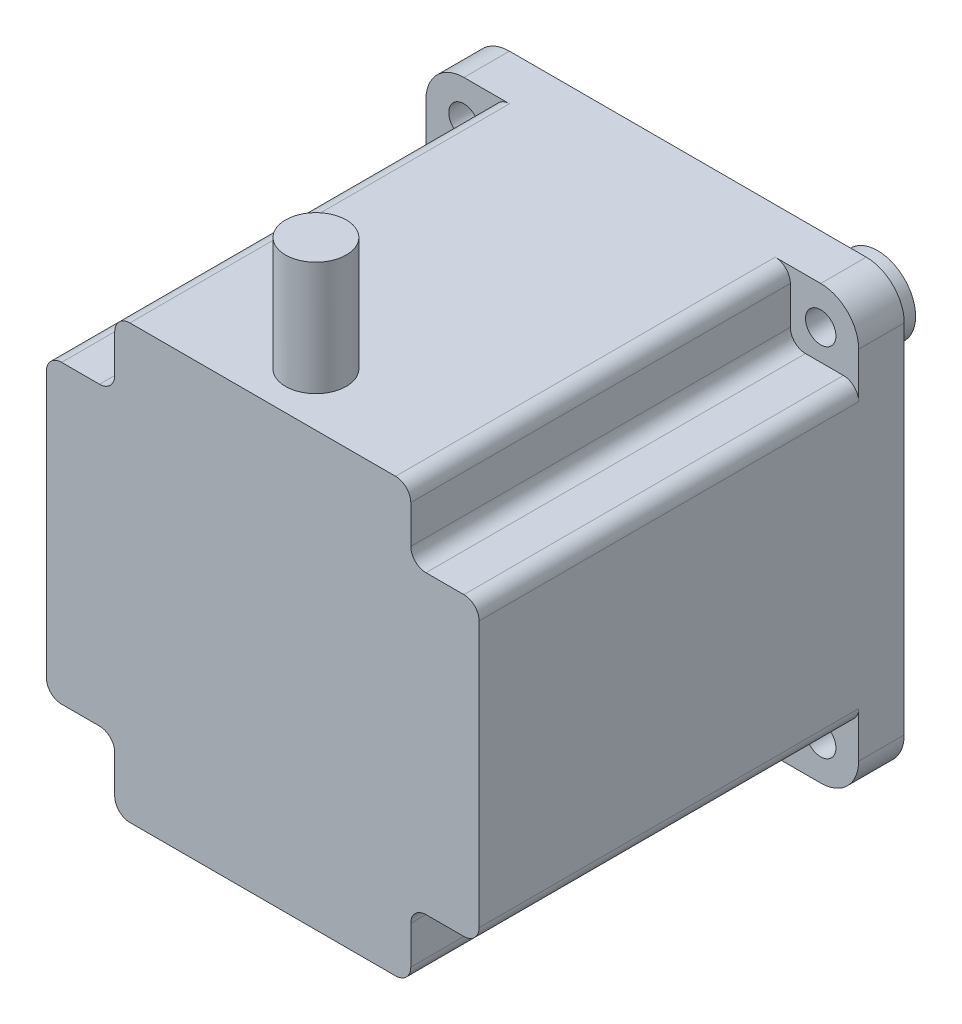
SolidWorks part; units mm, degrees
ref_plane "前视基准面" through (0, 0, 0) normal (0, 0, 1) x (1, 0, 0)
ref_plane "上视基准面" through (0, 0, 0) normal (0, 1, 0) x (1, 0, 0)
ref_plane "右视基准面" through (0, 0, 0) normal (1, 0, 0) x (0, 0, -1)
sketch "草图1" plane through (0, 0, 0) normal (0, 0, 1) x (1, 0, 0)
  line L1 (-23.5, 28.5) -> (23.5, 28.5)
  line L2 (-28.5, 23.5) -> (-28.5, -23.5)
  line L3 (-23.5, -28.5) -> (23.5, -28.5)
  line L4 (28.5, 23.5) -> (28.5, -23.5)
  line L5 (-27.0355, 27.0355) -> (27.0355, -27.0355) construction
  line L6 (-27.0355, -27.0355) -> (27.0355, 27.0355) construction
  arc A0 (-28.5, -23.5) -> (-23.5, -28.5) centre (-23.5, -23.5) ccw
  arc A1 (23.5, -28.5) -> (28.5, -23.5) centre (23.5, -23.5) ccw
  arc A2 (-23.5, 28.5) -> (-28.5, 23.5) centre (-23.5, 23.5) ccw
  arc A3 (28.5, 23.5) -> (23.5, 28.5) centre (23.5, 23.5) ccw
  point P0 (0, 0)
  dimension "D3" = 10
  dimension "D4" = 10
  dimension "D5" = 10
  dimension "D6" = 10
  dimension "D1" = 57
  dimension "D2" = 57
extrude "凸台-拉伸1" add sketch "草图1" along normal blind 56
sketch "草图2" plane through (0, 0, 56) normal (0, 0, 1) x (1, 0, 0)
  line L0 (-28.5, -19.5) -> (-19.5, -19.5)
  line L1 (-19.5, -19.5) -> (-19.5, -28.5)
  line L2 (-28.5, 19.5) -> (-19.5, 19.5)
  line L3 (-19.5, 19.5) -> (-19.5, 28.5)
  line L4 (23.5, 28.5) -> (-23.5, 28.5)
  line L5 (-28.5, 23.5) -> (-28.5, -23.5)
  line L6 (-23.5, -28.5) -> (23.5, -28.5)
  line L7 (28.5, -23.5) -> (28.5, 23.5)
  line L8 (23.5, 28.5) -> (19.5, 28.5)
  line L9 (-28.5, 23.5) -> (-28.5, 19.5)
  line L10 (-23.5, -28.5) -> (-19.5, -28.5)
  line L11 (28.5, -23.5) -> (28.5, -19.5)
  line L12 (28.5, 19.5) -> (19.5, 19.5)
  line L13 (19.5, 19.5) -> (19.5, 28.5)
  line L14 (19.5, -28.5) -> (19.5, -19.5)
  line L15 (19.5, -19.5) -> (28.5, -19.5)
  line L16 (-28.5, -19.5) -> (-28.5, -23.5)
  line L17 (28.5, 19.5) -> (28.5, 23.5)
  line L18 (19.5, -28.5) -> (23.5, -28.5)
  line L19 (-19.5, 28.5) -> (-23.5, 28.5)
  arc A4 (28.5, 23.5) -> (23.5, 28.5) centre (23.5, 23.5) ccw
  arc A5 (-23.5, 28.5) -> (-28.5, 23.5) centre (-23.5, 23.5) ccw
  arc A6 (-28.5, -23.5) -> (-23.5, -28.5) centre (-23.5, -23.5) ccw
  arc A7 (23.5, -28.5) -> (28.5, -23.5) centre (23.5, -23.5) ccw
  arc A8 (28.5, 23.5) -> (23.5, 28.5) centre (23.5, 23.5) ccw
  arc A9 (-23.5, 28.5) -> (-28.5, 23.5) centre (-23.5, 23.5) ccw
  arc A10 (-28.5, -23.5) -> (-23.5, -28.5) centre (-23.5, -23.5) ccw
  arc A11 (23.5, -28.5) -> (28.5, -23.5) centre (23.5, -23.5) ccw
  dimension "D2" = 9
  dimension "D3" = 9
  dimension "D4" = 9
  dimension "D5" = 9
  dimension "D6" = 9
  dimension "D7" = 9
  dimension "D1" = 0
extrude "切除-拉伸1" cut sketch "草图2" against normal blind 50
fillet "圆角1" radius 2 12 edges at (-19.5, 19.5, 31) (-19.5, -19.5, 31) (19.5, -19.5, 31) (19.5, 19.5, 31) (-19.5, -28.5, 31) (-28.5, -19.5, 31) (-28.5, 19.5, 31) (-19.5, 28.5, 31) (19.5, 28.5, 31) (28.5, 19.5, 31) (28.5, -19.5, 31) (19.5, -28.5, 31)
sketch "草图3" plane through (0, 0, 6) normal (0, 0, 1) x (1, 0, 0)
  circle A0 centre (-23.5, -23.5) radius 2
  circle A1 centre (-23.5, 23.5) radius 2
  circle A2 centre (23.5, 23.5) radius 2
  circle A3 centre (23.5, -23.5) radius 2
  dimension "D1" = 4
  dimension "D2" = 4
  dimension "D3" = 4
  dimension "D4" = 4
extrude "切除-拉伸2" cut sketch "草图3" against normal through all
sketch "草图4" plane through (0, 0, 0) normal (0, 0, -1) x (-1, 0, 0)
  circle A0 centre (0, 0) radius 5
  dimension "D1" = 10
extrude "凸台-拉伸2" add sketch "草图4" along normal blind 25
sketch "草图5" plane through (0, 28.5, 0) normal (0, 1, 0) x (1, 0, 0)
  line L0 (17.5, -56) -> (-17.5, -56) construction
  circle A0 centre (0, -49) radius 4
  dimension "D1" = 8
  dimension "D2" = 7
extrude "凸台-拉伸3" add sketch "草图5" along normal blind 15
